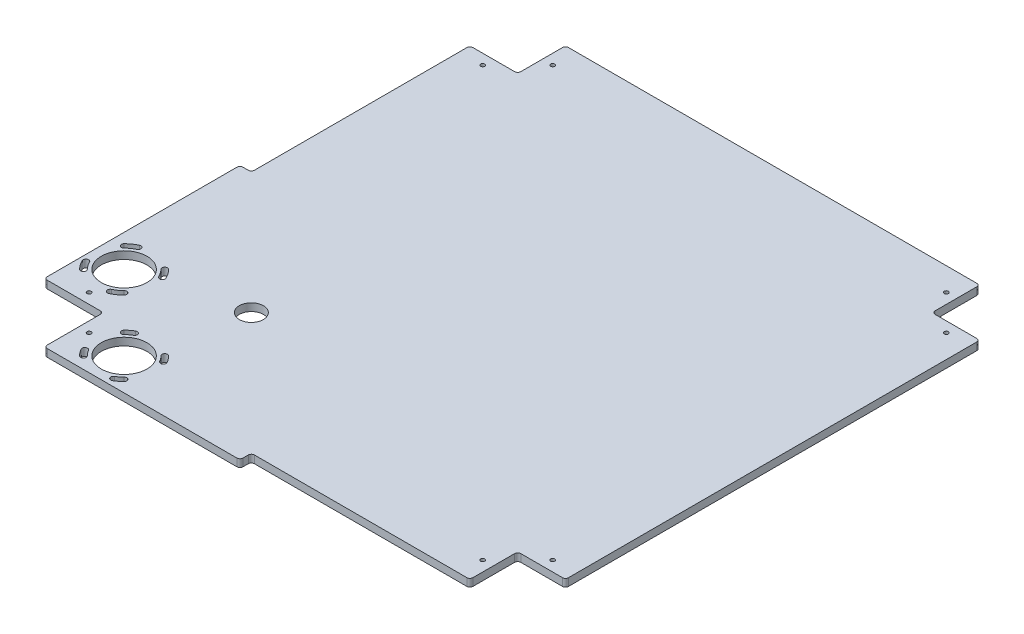
SolidWorks part; units mm, degrees
ref_plane "Front" through (0, 0, 0) normal (0, 0, 1) x (1, 0, 0)
ref_plane "Top" through (0, 0, 0) normal (0, 1, 0) x (1, 0, 0)
ref_plane "Right" through (0, 0, 0) normal (1, 0, 0) x (0, 0, -1)
sketch "Sketch1" plane through (0, 0, 0) normal (0, 1, 0) x (1, 0, 0)
  line L2 (212.725, -212.725) -> (212.725, 212.725)
  line L3 (212.725, 212.725) -> (-212.725, 212.725)
  line L5 (212.725, -212.725) -> (-212.725, 212.725) construction
  line L6 (212.725, 212.725) -> (-222.25, -222.25) construction
  line L7 (-222.25, -222.25) -> (-9.525, -222.25)
  line L8 (-9.525, -222.25) -> (-9.525, -212.725)
  line L9 (-9.525, -212.725) -> (212.725, -212.725)
  line L13 (-222.25, -222.25) -> (-222.25, -9.525)
  line L14 (-222.25, -9.525) -> (-212.725, -9.525)
  line L15 (-212.725, -9.525) -> (-212.725, 212.725)
  point P0 (0, 0)
  point P4 (-219.075, -28.0693)
  point P6 (-219.181, -174.9435)
  point P8 (-225.5039, -175.1713)
  point P11 (0, 0)
  point P12 (-203.2132, -209.5535)
  point P15 (0, 0)
  point P16 (-219.9748, -218.1752)
  point P17 (-219.9748, -210.6959)
  point P18 (-205.98, -210.4763)
  point P19 (-230.9959, -207.1541)
  point P20 (0, 0)
  point P21 (-220.8187, -226.72)
  point P22 (-218.7993, -219.3298)
  dimension "D3" = 9.525
  dimension "D6" = 425.45
  dimension "D7" = 425.45
  dimension "D8" = 222.25
extrude "Boss-Extrude1" add sketch "Sketch1" along normal blind 6.35
sketch "Sketch2" plane through (0, 6.35, 0) normal (0, 1, 0) x (1, 0, 0)
  line L0 (-212.725, 212.725) -> (-212.725, -9.525) construction
  line L1 (-9.525, -212.725) -> (212.725, -212.725) construction
  circle A1 centre (-111.125, -111.125) radius 10.033
  dimension "D1" = 20.066
  dimension "D3" = 101.6
  dimension "D2" = 101.6
extrude "Cut-Extrude1" cut sketch "Sketch2" against normal blind 9.525
sketch "Sketch3" plane through (0, 6.35, 0) normal (0, 1, 0) x (1, 0, 0)
  line L2 (-212.725, 212.725) -> (-172.847, 212.725)
  line L3 (-212.725, 212.725) -> (-212.725, 172.847)
  line L4 (-212.725, 172.847) -> (-172.847, 172.847)
  line L5 (-172.847, 212.725) -> (-172.847, 172.847)
  line L6 (212.725, 212.725) -> (172.847, 212.725)
  line L7 (212.725, 212.725) -> (212.725, 172.847)
  line L8 (212.725, 172.847) -> (172.847, 172.847)
  line L9 (172.847, 212.725) -> (172.847, 172.847)
  line L10 (212.725, -212.725) -> (172.847, -212.725)
  line L11 (212.725, -212.725) -> (212.725, -172.847)
  line L12 (212.725, -172.847) -> (172.847, -172.847)
  line L13 (172.847, -212.725) -> (172.847, -172.847)
  line L19 (-172.847, -172.847) -> (-224.6764, -172.847)
  line L20 (-172.847, -172.847) -> (-172.847, -223.8399)
  line L21 (-172.847, -223.8399) -> (-224.6764, -223.8399)
  line L22 (-224.6764, -172.847) -> (-224.6764, -223.8399)
  dimension "D1" = 39.878
  dimension "D2" = 39.878
  dimension "D3" = 345.694
  dimension "D4" = 345.694
  dimension "D5" = 39.878
  dimension "D6" = 39.878
  dimension "D7" = 39.878
  dimension "D8" = 39.878
  dimension "D9" = 51.8294
  dimension "D10" = 50.9929
extrude "Cut-Extrude2" cut sketch "Sketch3" against normal through all
fillet "Fillet1" radius 2.54 16 edges at (-172.847, 3.175, -172.847) (-172.847, 3.175, -212.725) (212.725, 3.175, -172.847) (172.847, 3.175, -172.847) (172.847, 3.175, -212.725) (212.725, 3.175, 172.847) (172.847, 3.175, 172.847) (-9.525, 3.175, 212.725) (-9.525, 3.175, 222.25) (172.847, 3.175, 212.725) (-222.25, 3.175, 9.525) (-212.725, 3.175, 9.525) (-212.725, 3.175, -172.847) (-172.847, 3.175, 172.847) (-222.25, 3.175, 172.847) (-172.847, 3.175, 222.25)
hole_wizard "M3 Clearance Hole1" positions "Sketch5" profile "Sketch4" hole size "M3" standard "ANSI Metric" end condition through all
sketch "Sketch5" plane through (0, 6.35, 0) normal (0, 1, 0) x (1, 0, 0)
  line L4 (172.847, -175.387) -> (172.847, -210.185) construction
  line L5 (210.185, -172.847) -> (175.387, -172.847) construction
  line L6 (212.725, -170.307) -> (212.725, 170.307) construction
  line L7 (170.307, 212.725) -> (-170.307, 212.725) construction
  line L8 (-172.847, 175.387) -> (-172.847, 210.185) construction
  line L9 (-210.185, 172.847) -> (-175.387, 172.847) construction
  line L10 (172.847, 210.185) -> (172.847, 175.387) construction
  line L11 (175.387, 172.847) -> (210.185, 172.847) construction
  line L12 (-6.985, -212.725) -> (170.307, -212.725) construction
  line L13 (-172.847, -219.71) -> (-172.847, -175.387) construction
  line L14 (-175.387, -172.847) -> (-219.71, -172.847) construction
  line L15 (-212.725, 170.307) -> (-212.725, -6.985) construction
  circle A0 centre (164.211, -193.421) radius 1.651
  circle A1 centre (193.421, -164.211) radius 1.651
  circle A2 centre (164.211, 193.421) radius 1.651
  circle A3 centre (193.421, 164.211) radius 1.651
  circle A4 centre (-164.211, 193.421) radius 1.651
  circle A5 centre (-193.421, 164.211) radius 1.651
  point P0 (-164.211, -193.421)
  point P15 (-193.421, -164.211)
  point P58 (-193.421, 164.211)
  point P61 (-164.211, 193.421)
  point P64 (164.211, 193.421)
  point P67 (193.421, 164.211)
  point P70 (193.421, -164.211)
  point P73 (164.211, -193.421)
  dimension "D5" = 3.302
  dimension "D6" = 3.302
  dimension "D7" = 19.304
  dimension "D8" = 8.636
  dimension "D9" = 8.636
  dimension "D10" = 19.304
  dimension "D11" = 3.302
  dimension "D12" = 3.302
  dimension "D13" = 19.304
  dimension "D14" = 8.636
  dimension "D15" = 8.636
  dimension "D16" = 19.304
  dimension "D17" = 3.302
  dimension "D18" = 3.302
  dimension "D19" = 8.636
  dimension "D20" = 19.304
  dimension "D21" = 19.304
  dimension "D22" = 8.636
  dimension "D23" = 8.636
  dimension "D24" = 19.304
  dimension "D3" = 8.636
  dimension "D4" = 19.304
sketch "Sketch4" plane through (-164.211, 6.35, 193.421) normal (1, 0, 0) x (0, 0, 1)
  line L0 (0, 0) -> (0, 6.35)
  line L1 (0, 6.35) -> (1.7, 6.35)
  line L2 (1.7, 6.35) -> (1.7, 0)
  line L5 (1.7, 0) -> (0, 0)
  line L11 (0, -6.35) -> (0, 107.95) construction
  dimension "Thru Hole Dia." = 3.4
  dimension "Thru Hole Depth" = 6.35
sketch "Sketch6" plane through (0, 6.35, 0) normal (0, 1, 0) x (1, 0, 0)
  line L2 (-212.725, 170.307) -> (-212.725, -6.985) construction
  line L3 (-6.985, -212.725) -> (170.307, -212.725) construction
  arc A1 (-178.4803, -149.9417) -> (-185.3089, -154.7231) centre (-195.453, -132.969) cw construction
  arc A2 (-184.3428, -156.7949) -> (-176.8639, -151.5581) centre (-195.453, -132.969) ccw
  arc A3 (-115.9963, -178.4803) -> (-112.1818, -183.4515) centre (-132.969, -195.453) cw construction
  arc A5 (-186.275, -152.6513) -> (-180.0968, -148.3252) centre (-195.453, -132.969) ccw
  circle A6 centre (-195.453, -132.969) radius 19.05
  circle A7 centre (-132.969, -195.453) radius 19.05
  arc A8 (-212.4257, -149.9417) -> (-217.2071, -143.1131) centre (-195.453, -132.969) cw construction
  arc A9 (-186.275, -152.6513) -> (-184.3428, -156.7949) centre (-185.3089, -154.7231) ccw
  arc A10 (-176.8639, -151.5581) -> (-180.0968, -148.3252) centre (-178.4803, -149.9417) ccw
  arc A11 (-110.2021, -182.3085) -> (-114.3799, -176.8639) centre (-132.969, -195.453) ccw
  arc A12 (-219.2789, -144.0792) -> (-214.0421, -151.5581) centre (-195.453, -132.969) ccw
  arc A13 (-114.1615, -184.5945) -> (-117.6128, -180.0968) centre (-132.969, -195.453) ccw
  arc A14 (-215.1353, -142.147) -> (-210.8092, -148.3252) centre (-195.453, -132.969) ccw
  arc A16 (-215.1353, -142.147) -> (-219.2789, -144.0792) centre (-217.2071, -143.1131) ccw
  arc A17 (-214.0421, -151.5581) -> (-210.8092, -148.3252) centre (-212.4257, -149.9417) ccw
  arc A18 (-212.4257, -115.9963) -> (-205.5971, -111.2149) centre (-195.453, -132.969) cw construction
  arc A19 (-206.5632, -109.1431) -> (-214.0421, -114.3799) centre (-195.453, -132.969) ccw
  arc A21 (-204.631, -113.2867) -> (-210.8092, -117.6128) centre (-195.453, -132.969) ccw
  arc A22 (-204.631, -113.2867) -> (-206.5632, -109.1431) centre (-205.5971, -111.2149) ccw
  arc A23 (-214.0421, -114.3799) -> (-210.8092, -117.6128) centre (-212.4257, -115.9963) ccw
  arc A24 (-178.4803, -115.9963) -> (-173.6989, -122.8249) centre (-195.453, -132.969) cw construction
  arc A25 (-171.6271, -121.8588) -> (-176.8639, -114.3799) centre (-195.453, -132.969) ccw
  arc A26 (-175.7707, -123.791) -> (-180.0968, -117.6128) centre (-195.453, -132.969) ccw
  arc A27 (-175.7707, -123.791) -> (-171.6271, -121.8588) centre (-173.6989, -122.8249) ccw
  arc A28 (-176.8639, -114.3799) -> (-180.0968, -117.6128) centre (-178.4803, -115.9963) ccw
  arc A29 (-114.1615, -184.5945) -> (-110.2021, -182.3085) centre (-112.1818, -183.4515) ccw
  arc A30 (-114.3799, -176.8639) -> (-117.6128, -180.0968) centre (-115.9963, -178.4803) ccw
  arc A31 (-115.9963, -212.4257) -> (-120.9675, -216.2402) centre (-132.969, -195.453) cw construction
  arc A32 (-119.8245, -218.2199) -> (-114.3799, -214.0421) centre (-132.969, -195.453) ccw
  arc A33 (-122.1105, -214.2605) -> (-117.6128, -210.8092) centre (-132.969, -195.453) ccw
  arc A34 (-122.1105, -214.2605) -> (-119.8245, -218.2199) centre (-120.9675, -216.2402) ccw
  arc A35 (-114.3799, -214.0421) -> (-117.6128, -210.8092) centre (-115.9963, -212.4257) ccw
  arc A36 (-149.9417, -212.4257) -> (-153.7562, -207.4545) centre (-132.969, -195.453) cw construction
  arc A37 (-155.7359, -208.5975) -> (-151.5581, -214.0421) centre (-132.969, -195.453) ccw
  arc A38 (-151.7765, -206.3115) -> (-148.3252, -210.8092) centre (-132.969, -195.453) ccw
  arc A39 (-151.7765, -206.3115) -> (-155.7359, -208.5975) centre (-153.7562, -207.4545) ccw
  arc A40 (-151.5581, -214.0421) -> (-148.3252, -210.8092) centre (-149.9417, -212.4257) ccw
  arc A41 (-149.9417, -178.4803) -> (-144.9705, -174.6658) centre (-132.969, -195.453) cw construction
  arc A42 (-146.1135, -172.6861) -> (-151.5581, -176.8639) centre (-132.969, -195.453) ccw
  arc A43 (-143.8275, -176.6455) -> (-148.3252, -180.0968) centre (-132.969, -195.453) ccw
  arc A44 (-143.8275, -176.6455) -> (-146.1135, -172.6861) centre (-144.9705, -174.6658) ccw
  arc A45 (-151.5581, -176.8639) -> (-148.3252, -180.0968) centre (-149.9417, -178.4803) ccw
  point P1 (-181.6854, -152.6311)
  point P10 (-105.38, -157.3604)
  point P18 (-113.9261, -180.8409)
  point P19 (0, 0)
  point P20 (0, 0)
  point P25 (-215.1151, -146.7366)
  point P29 (-130.175, -193.675)
  point P37 (-195.453, -132.969)
  point P38 (-195.453, -132.969)
  point P39 (-209.2206, -113.3069)
  point P48 (-175.7909, -119.2014)
  point P52 (-132.969, -195.453)
  point P57 (-195.453, -132.969)
  point P61 (-118.3569, -214.4959)
  point P68 (-152.0119, -210.0651)
  point P75 (-147.5811, -176.4101)
  point P80 (-132.969, -195.453)
  dimension "D4" = 17.272
  dimension "D3" = 79.756
  dimension "D5" = 79.756
  dimension "D6" = 4
  dimension "D7" = 24.003
  dimension "D8" = 38.1
  dimension "D9" = 2.286
  dimension "D10" = 38.1
  dimension "D11" = 2.286
  dimension "D2" = 17.272
  dimension "D12" = 24.003
  dimension "D13" = 4
  dimension "D14" = 6.266
extrude "Cut-Extrude3" cut sketch "Sketch6" against normal through all
hole_wizard "M4 Clearance Hole1" [suppressed] positions "Sketch8" profile "Sketch7" hole size "M4" standard "ANSI Metric"
sketch "Sketch8" [suppressed] plane through (0, 6.35, 0) normal (0, 1, 0) x (1, 0, 0)
  line L0 (30.7719, 54.5603) -> (64.713, 88.5014) construction
  line L3 (64.713, 54.5603) -> (30.7719, 88.5014) construction
  line L5 (68.2448, 28.561) -> (102.1859, -5.3801) construction
  line L8 (102.1859, 28.561) -> (68.2448, -5.3801) construction
  circle A0 centre (47.7425, 71.5308) radius 24 construction
  circle A1 centre (85.2154, 11.5904) radius 24 construction
  point P0 (30.7719, 54.5603)
  point P2 (64.713, 54.5603)
  point P4 (64.713, 88.5014)
  point P6 (30.7719, 88.5014)
  point P22 (102.1859, 28.561)
  point P24 (68.2448, -5.3801)
  point P26 (68.2448, 28.561)
  point P28 (102.1859, -5.3801)
  dimension "D1" = 48
  dimension "D2" = 48
  dimension "D3" = 90
  dimension "D4" = 90
sketch "Sketch7" plane through (30.7719, 6.35, -54.5603) normal (1, 0, 0) x (0, 0, 1)
  line L0 (0, 0) -> (0, 6.35)
  line L1 (0, 6.35) -> (2.25, 6.35)
  line L2 (2.25, 6.35) -> (2.25, 0)
  line L5 (2.25, 0) -> (0, 0)
  line L11 (0, -6.35) -> (0, 107.95) construction
  dimension "Thru Hole Dia." = 4.5
  dimension "Thru Hole Depth" = 6.35
equation "\"D2@Sketch2\"=\"D3@Sketch2\""
